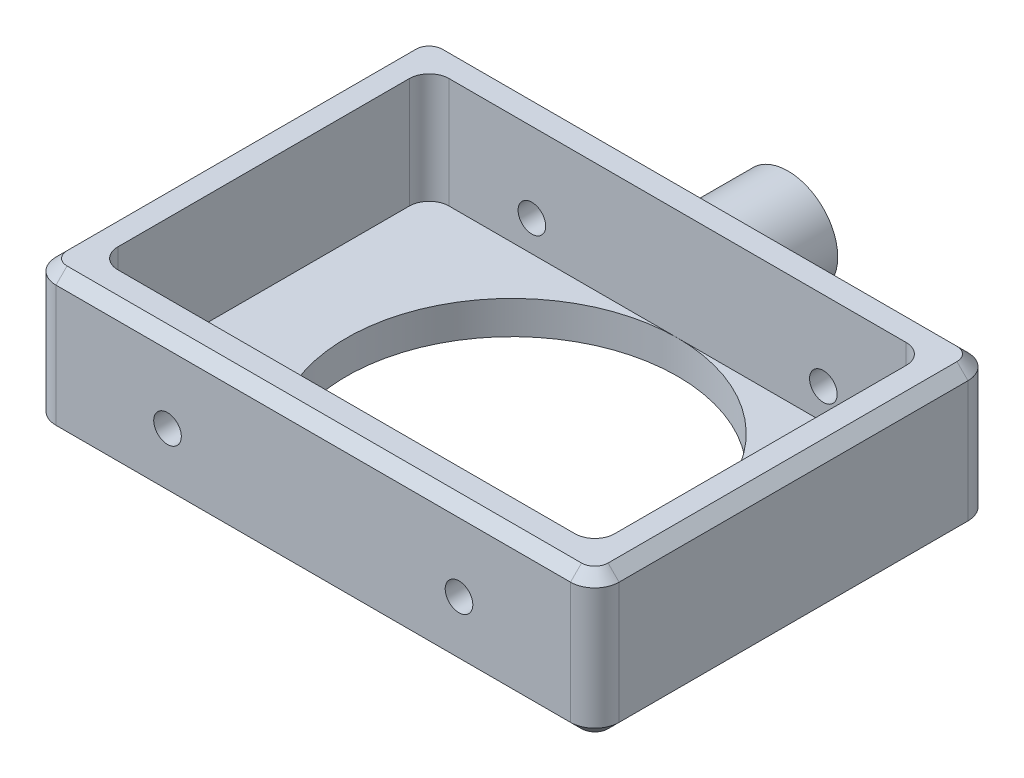
SolidWorks part; units mm, degrees
ref_plane "Front Plane" through (0, 0, 0) normal (0, 0, 1) x (1, 0, 0)
ref_plane "Top Plane" through (0, 0, 0) normal (0, 1, 0) x (1, 0, 0)
ref_plane "Right Plane" through (0, 0, 0) normal (1, 0, 0) x (0, 0, -1)
sketch "Sketch1" plane through (0, 0, 0) normal (0, 1, 0) x (1, 0, 0)
  line L1 (-25.5, -18) -> (25.5, -18)
  line L2 (-25.5, -18) -> (-25.5, 18)
  line L3 (-25.5, 18) -> (25.5, 18)
  line L4 (25.5, -18) -> (25.5, 18)
  line L5 (-25.5, -18) -> (25.5, 18) construction
  line L6 (-25.5, 18) -> (25.5, -18) construction
  point P0 (0, 0)
  dimension "D1" = 51
  dimension "D2" = 36
extrude "Boss-Extrude1" add sketch "Sketch1" along normal blind 3
sketch "Sketch2" plane through (0, 3, 0) normal (0, 1, 0) x (1, 0, 0)
  line L0 (25.5, -18) -> (25.5, 18) construction
  line L1 (-25.5, 18) -> (25.5, 18)
  line L2 (-25.5, 18) -> (-25.5, 15)
  line L3 (-22.5, 15) -> (22.5, 15)
  line L4 (25.5, 18) -> (25.5, 15)
  line L5 (-25.5, -18) -> (25.5, -18) construction
  line L6 (-25.5, 18) -> (-22.5, 18)
  line L7 (-25.5, 18) -> (-25.5, -18)
  line L8 (-25.5, -18) -> (-22.5, -18)
  line L9 (-22.5, 15) -> (-22.5, -15)
  line L11 (25.5, 18) -> (22.5, 18)
  line L12 (25.5, 18) -> (25.5, -18)
  line L13 (25.5, -18) -> (22.5, -18)
  line L14 (22.5, 15) -> (22.5, -15)
  line L15 (-25.5, -18) -> (25.5, -18)
  line L16 (-25.5, -18) -> (-25.5, -15)
  line L17 (-22.5, -15) -> (22.5, -15)
  line L18 (25.5, -18) -> (25.5, -15)
  line M1 (25.5, -18) -> (25.5, 18)
  line M2 (25.5, 18) -> (-25.5, 18)
  line M3 (-25.5, 18) -> (-25.5, -18)
  line M4 (-25.5, -18) -> (25.5, -18)
  dimension "D1" = 3
  dimension "D2" = 3
  dimension "D3" = 3
  dimension "D4" = 3
extrude "Boss-Extrude2" add sketch "Sketch2" along normal blind 10 contours L12 L1 L7 L17 L9 L3 L14 M4 M1 M2 M3
fillet "Fillet1" radius 1.8 4 edges at (22.5, 8, 15) (-22.5, 8, 15) (22.5, 8, -15) (-22.5, 8, -15)
fillet "Fillet2" radius 2.2 4 edges at (-25.5, 6.5, -18) (-25.5, 6.5, 18) (25.5, 6.5, -18) (25.5, 6.5, 18)
chamfer "Chamfer1" distance 1 angle 45 8 edges at (24.8556, 0, 17.3556) (0, 0, 18) (25.5, 0, 0) (-24.8556, 0, 17.3556) (24.8556, 0, -17.3556) (-25.5, 0, 0) (-24.8556, 0, -17.3556) (0, 0, -18)
sketch "Sketch3" plane through (0, 3, 0) normal (0, 1, 0) x (1, 0, 0)
  circle A0 centre (0, 0) radius 15
  dimension "D1" = 30
extrude "Cut-Extrude1" cut sketch "Sketch3" against normal blind 10
sketch "Sketch4" plane through (0, 0, 18) normal (0, 0, 1) x (1, 0, 0)
  line L0 (-22.5, 13) -> (-22.5, 3) construction
  line L1 (22.5, 3) -> (22.5, 13) construction
  line L2 (0, 3) -> (20.7, 3) construction
  line L3 (-20.7, 3) -> (0, 3) construction
  circle A0 centre (-13.2, 5.8) radius 1.25
  circle A1 centre (13.2, 5.8) radius 1.25
  dimension "D1" = 2.5
  dimension "D2" = 2.5
  dimension "D3" = 9.3
  dimension "D4" = 9.3
  dimension "D5" = 2.8
  dimension "D6" = 2.8
extrude "Cut-Extrude2" cut sketch "Sketch4" against normal blind 50
chamfer "Chamfer2" distance 1 angle 45 8 edges at (0, 13, -18) (-24.8556, 13, -17.3556) (24.8556, 13, -17.3556) (-25.5, 13, 0) (25.5, 13, 0) (-24.8556, 13, 17.3556) (24.8556, 13, 17.3556) (0, 13, 18)
sketch "Sketch5" plane through (0, 0, -18) normal (0, 0, -1) x (-1, 0, 0)
  line L0 (-23.3, 1) -> (23.3, 1) construction
  circle A0 centre (0, 6.6) radius 4.5
  dimension "D1" = 9
  dimension "D2" = 5.6
extrude "Boss-Extrude3" add sketch "Sketch5" along normal blind 7
